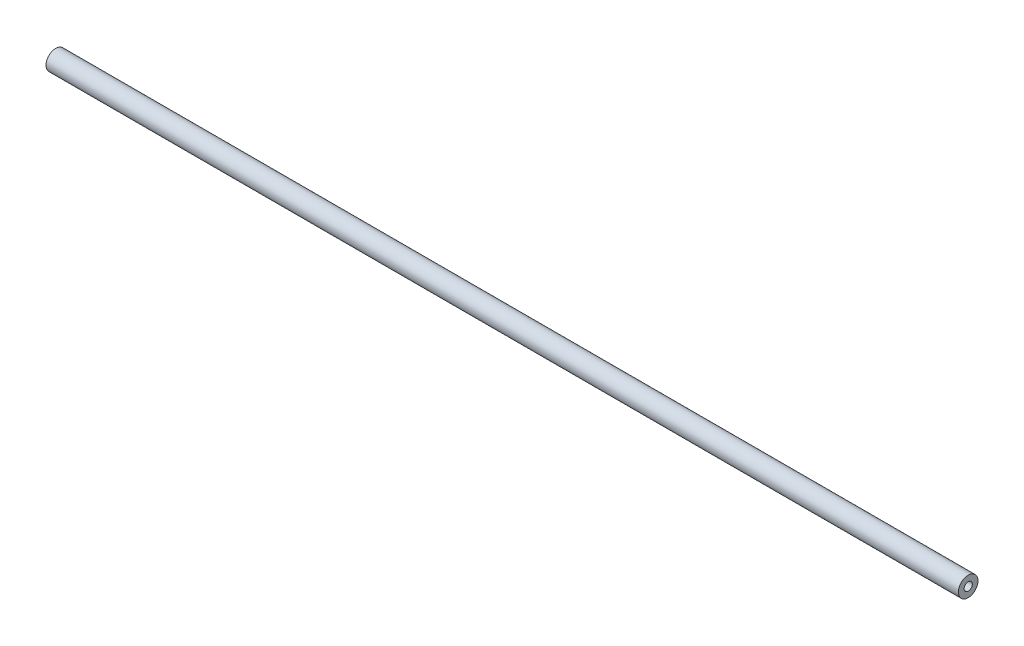
SolidWorks part; units mm, degrees
material "6061-T6 (SS)"
ref_plane "Front Plane" through (0, 0, 0) normal (0, 0, 1) x (1, 0, 0)
ref_plane "Top Plane" through (0, 0, 0) normal (0, 1, 0) x (1, 0, 0)
ref_plane "Right Plane" through (0, 0, 0) normal (1, 0, 0) x (0, 0, -1)
sketch "Sketch1" plane through (0, 0, 0) normal (1, 0, 0) x (0, 0, -1)
  circle A0 centre (0, 0) radius 4.7625
  circle A1 centre (0, 0) radius 1.9939
  dimension "D1" = 9.525
  dimension "D2" = 3.9878
extrude "Boss-Extrude1" add sketch "Sketch1" along normal mid plane 444.5
